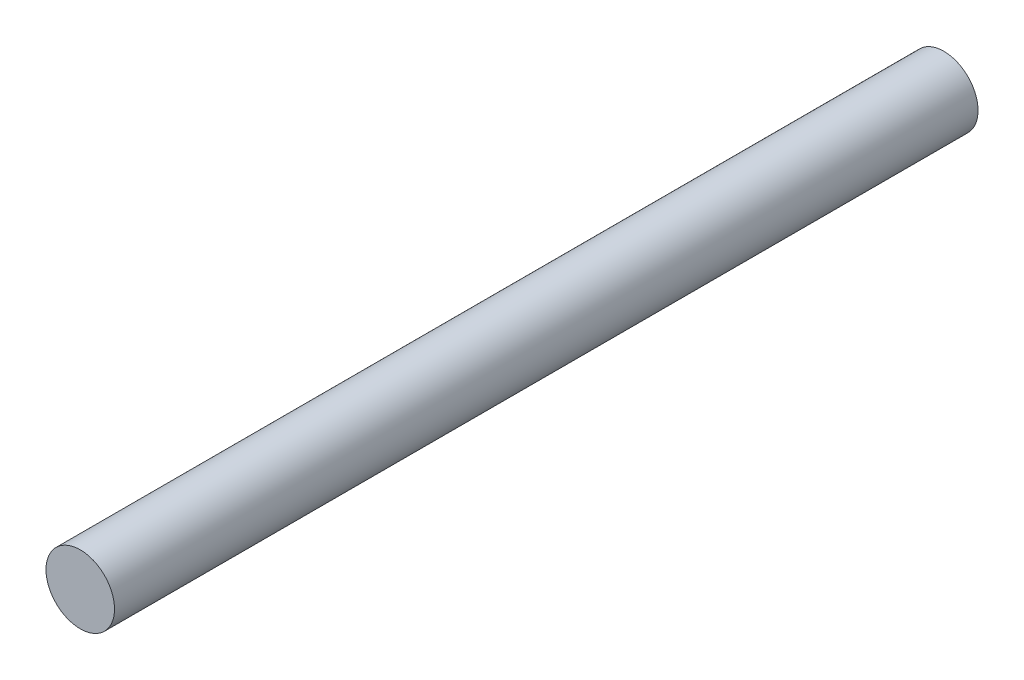
SolidWorks part; units mm, degrees
ref_plane "Front Plane" through (0, 0, 0) normal (0, 0, 1) x (1, 0, 0)
ref_plane "Top Plane" through (0, 0, 0) normal (0, 1, 0) x (1, 0, 0)
ref_plane "Right Plane" through (0, 0, 0) normal (1, 0, 0) x (0, 0, -1)
sketch "Sketch1" plane through (0, 0, 0) normal (0, 0, 1) x (1, 0, 0)
  circle A0 centre (0, 0) radius 12.5
  dimension "D1" = 25
extrude "Boss-Extrude1" add sketch "Sketch1" along normal blind 315.08
